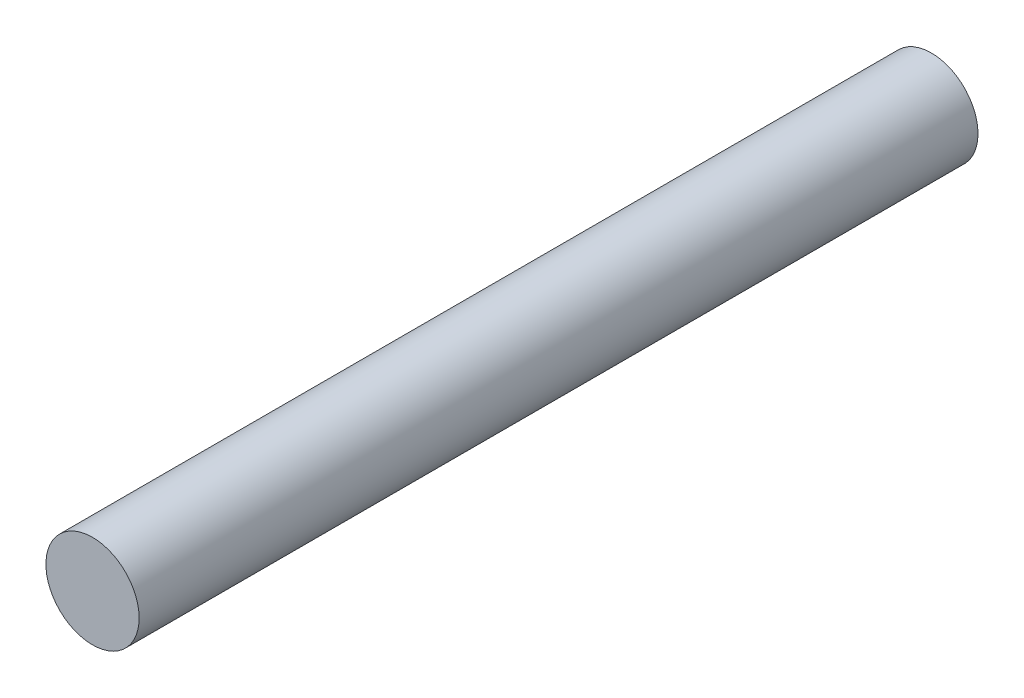
SolidWorks part; units mm, degrees
ref_plane "前视基准面" through (0, 0, 0) normal (0, 0, 1) x (1, 0, 0)
ref_plane "上视基准面" through (0, 0, 0) normal (0, 1, 0) x (1, 0, 0)
ref_plane "右视基准面" through (0, 0, 0) normal (1, 0, 0) x (0, 0, -1)
sketch "草图1" plane through (0, 0, 0) normal (0, 0, 1) x (1, 0, 0)
  circle A0 centre (-11.4454, 3.6055) radius 3.5
extrude "凸台-拉伸1" add sketch "草图1" along normal blind 63
